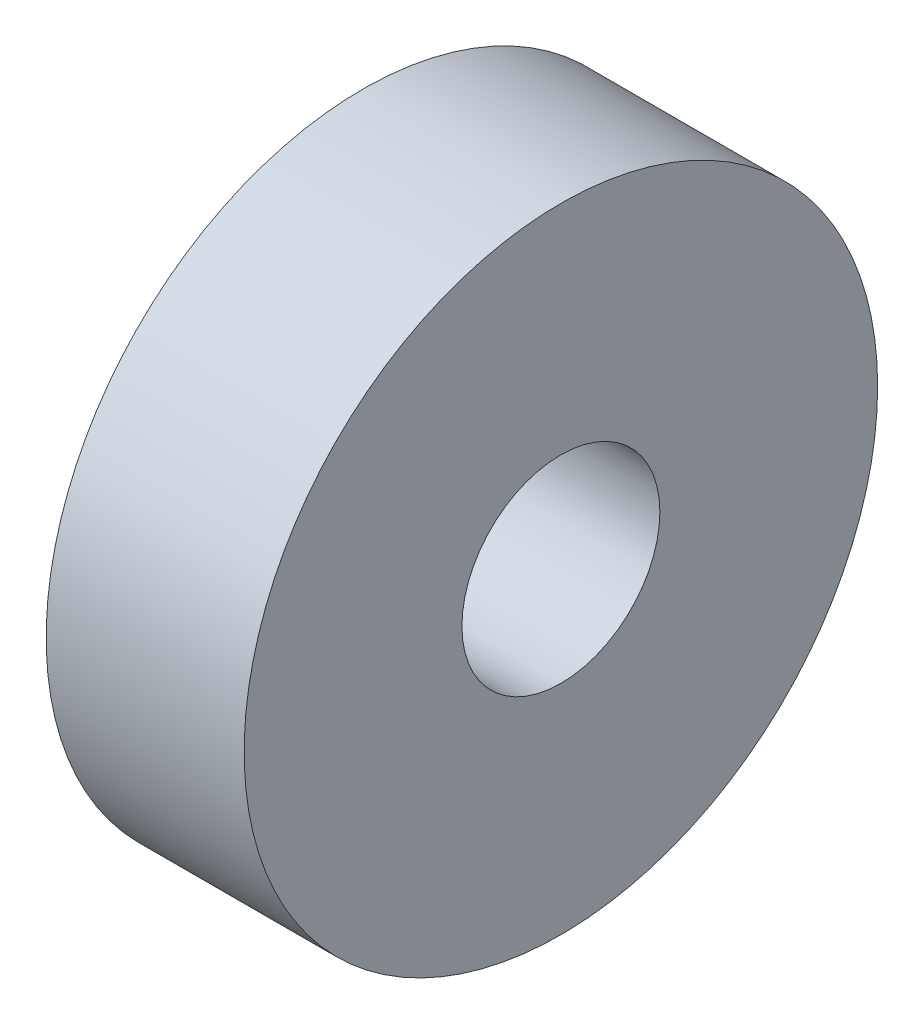
SolidWorks part; units mm, degrees
ref_plane "Front" through (0, 0, 0) normal (0, 0, 1) x (1, 0, 0)
ref_plane "Top" through (0, 0, 0) normal (0, 1, 0) x (1, 0, 0)
ref_plane "Right" through (0, 0, 0) normal (1, 0, 0) x (0, 0, -1)
sketch "Sketch1" plane through (0, 0, 0) normal (1, 0, 0) x (0, 0, -1)
  circle A0 centre (0, 0) radius 8
  circle A1 centre (0, 0) radius 2.5
  dimension "D1" = 5
  dimension "D2" = 16
extrude "Boss-Extrude1" add sketch "Sketch1" along normal blind 5
